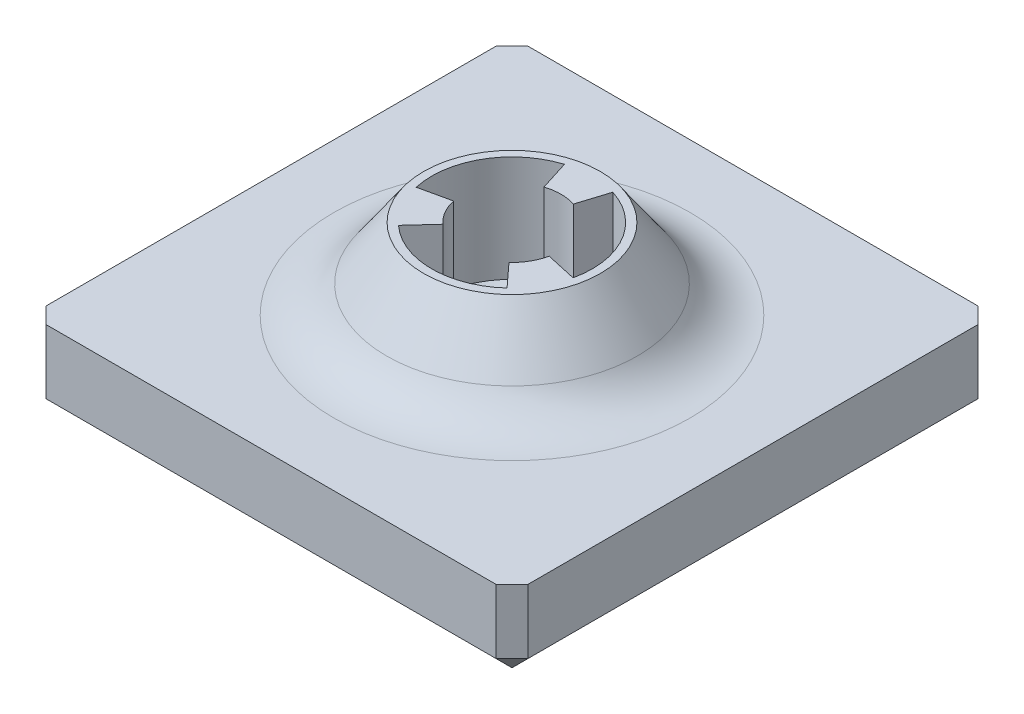
SolidWorks part; units mm, degrees
ref_plane "Front Plane" through (0, 0, 0) normal (0, 0, 1) x (1, 0, 0)
ref_plane "Top Plane" through (0, 0, 0) normal (0, 1, 0) x (1, 0, 0)
ref_plane "Right Plane" through (0, 0, 0) normal (1, 0, 0) x (0, 0, -1)
sketch "Sketch1" plane through (0, 0, 0) normal (0, 1, 0) x (1, 0, 0)
  line L1 (-15, 15) -> (15, 15)
  line L2 (-15, 15) -> (-15, -15)
  line L3 (-15, -15) -> (15, -15)
  line L4 (15, 15) -> (15, -15)
  line L5 (-15, 15) -> (15, -15) construction
  line L6 (-15, -15) -> (15, 15) construction
  point P0 (0, 0)
  dimension "D1" = 30
  dimension "D2" = 30
extrude "Boss-Extrude1" add sketch "Sketch1" along normal blind 5
sketch "Sketch2" plane through (0, 5, 0) normal (0, 1, 0) x (1, 0, 0)
  circle A0 centre (0, 0) radius 9
  dimension "D1" = 18
extrude "Boss-Extrude2" add sketch "Sketch2" along normal blind 5.8 draft 35
sketch "Sketch4" plane through (0, 10.8, 0) normal (0, 1, 0) x (1, 0, 0)
  circle A0 centre (0, 0) radius 5
  dimension "D1" = 10
extrude "Cut-Extrude2" cut sketch "Sketch4" against normal blind 8
sketch "Sketch5" plane through (0, 2.8, 0) normal (0, 1, 0) x (1, 0, 0)
  line L0 (0, 3.05) -> (0, -5.1) construction
  line L1 (-1.5336, 4.864) -> (-0.9172, 2.9088)
  line L4 (1.5336, 4.864) -> (0.9172, 2.9088)
  line L14 (3.4455, -3.7601) -> (2.0606, -2.2487)
  line L15 (4.9791, -1.1038) -> (2.9777, -0.6601)
  line L16 (-4.9791, -1.1038) -> (-2.9777, -0.6601)
  line L17 (-3.4455, -3.7601) -> (-2.0606, -2.2487)
  circle A0 centre (0, 0) radius 5.1 construction
  circle A1 centre (0, 0) radius 3.05 construction
  arc A2 (-0.9172, 2.9088) -> (0.9172, 2.9088) centre (0, 0) cw
  arc A5 (-1.5336, 4.864) -> (1.5336, 4.864) centre (0, 0) cw
  arc A6 (4.9791, -1.1038) -> (3.4455, -3.7601) centre (0, 0) cw
  arc A7 (2.9777, -0.6601) -> (2.0606, -2.2487) centre (0, 0) cw
  arc A8 (-3.4455, -3.7601) -> (-4.9791, -1.1038) centre (0, 0) cw
  arc A9 (-2.0606, -2.2487) -> (-2.9777, -0.6601) centre (0, 0) cw
  dimension "D1" = 6.1
  dimension "D2" = 10.2
  dimension "D3" = 35
  dimension "D4" = 3
extrude "Boss-Extrude3" add sketch "Sketch5" along normal blind 7.5
chamfer "Chamfer1" distance 1 angle 45 8 edges at (0, 0, -15) (-15, 2.5, -15) (-15, 0, 0) (15, 2.5, -15) (15, 0, 0) (15, 2.5, 15) (0, 0, 15) (-15, 2.5, 15)
fillet "Fillet2" radius 4 1 edges at (0, 5, 9)
sketch "Sketch6" plane through (0, 0, 15) normal (0, 0, 1) x (1, 0, 0)
  line L0 (14, 0) -> (-14, 0) construction
  line L1 (-15, 12) -> (15, 12)
  line L2 (-15, 12) -> (-15, 10)
  line L3 (-15, 10) -> (15, 10)
  line L4 (15, 12) -> (15, 10)
  line L5 (-14, 5) -> (14, 5) construction
  point P4 (0, 10)
  point P7 (0, 0)
  dimension "D1" = 2
  dimension "D2" = 30
  dimension "D3" = 5
extrude "Cut-Extrude3" cut sketch "Sketch6" against normal through all
chamfer "Chamfer2" distance 0.6 angle 45 12 edges at (-3.9296, 2.8, 0.8712) (-4.3301, 2.8, -2.5) (-1.2103, 2.8, -3.8387) (0, 2.8, -3.05) (1.2103, 2.8, -3.8387) (4.3301, 2.8, -2.5) (3.9296, 2.8, 0.8712) (2.6414, 2.8, 1.525) (2.7193, 2.8, 2.9675) (0, 2.8, 5) (-2.7193, 2.8, 2.9675) (-2.6414, 2.8, 1.525)
